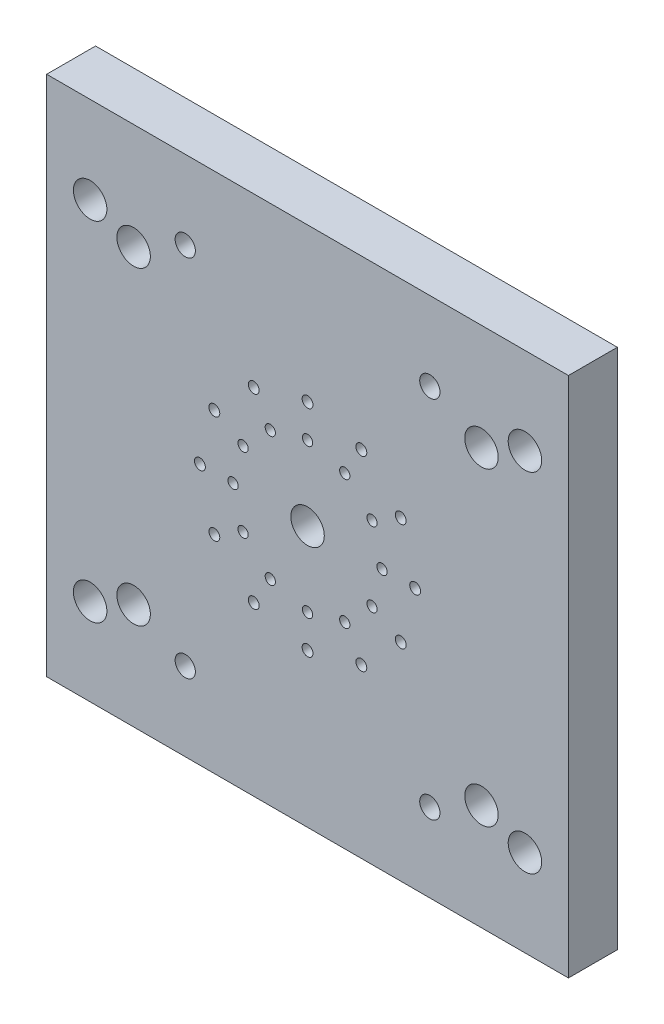
SolidWorks part; units mm, degrees
ref_plane "Front Plane" through (0, 0, 0) normal (0, 0, 1) x (1, 0, 0)
ref_plane "Top Plane" through (0, 0, 0) normal (0, 1, 0) x (1, 0, 0)
ref_plane "Right Plane" through (0, 0, 0) normal (1, 0, 0) x (0, 0, -1)
sketch "Sketch1" plane through (0, 0, 0) normal (0, 0, 1) x (1, 0, 0)
  line L1 (-152.4, 152.4) -> (152.4, 152.4)
  line L2 (-152.4, 152.4) -> (-152.4, -152.4)
  line L3 (-152.4, -152.4) -> (152.4, -152.4)
  line L4 (152.4, 152.4) -> (152.4, -152.4)
  line L5 (-152.4, 152.4) -> (152.4, -152.4) construction
  line L6 (-152.4, -152.4) -> (152.4, 152.4) construction
  point P0 (0, 0)
  dimension "D1" = 304.8
  dimension "D2" = 304.8
extrude "Boss-Extrude1" add sketch "Sketch1" along normal blind 28.575
sketch "Sketch2" plane through (0, 0, 28.575) normal (0, 0, 1) x (1, 0, 0)
  line L0 (-152.4, 0) -> (152.4, 0) construction
  line L5 (-152.4, 152.4) -> (-152.4, -152.4) construction
  line L6 (152.4, -152.4) -> (152.4, 152.4) construction
  line L7 (-152.4, -101.6) -> (152.4, -101.6) construction
  line L8 (-152.4, 101.6) -> (152.4, 101.6) construction
  line L9 (0, 101.6) -> (0, -101.6) construction
  line L10 (127, 101.6) -> (127, -101.6) construction
  line L11 (-127, 101.6) -> (-127, -101.6) construction
  circle A0 centre (-127, 101.6) radius 6.5151
  circle A1 centre (127, 101.6) radius 6.5151
  circle A2 centre (127, -101.6) radius 6.5151
  circle A3 centre (-127, -101.6) radius 6.5151
  circle A4 centre (0, 0) radius 6.5151
  dimension "D5" = 13.0302
  dimension "D1" = 101.6
  dimension "D2" = 101.6
  dimension "D3" = 127
  dimension "D4" = 127
extrude "HAAS T-Slot Holes" cut sketch "Sketch2" against normal through all
sketch "Sketch3" plane through (0, 0, 28.575) normal (0, 0, 1) x (1, 0, 0)
  circle A0 centre (-127, 101.6) radius 9.779
  circle A1 centre (127, 101.6) radius 9.779
  circle A2 centre (0, 0) radius 9.779
  circle A3 centre (127, -101.6) radius 9.779
  circle A4 centre (-127, -101.6) radius 9.779
  dimension "D1" = 19.558
extrude "HAAS Counter Bores" cut sketch "Sketch3" against normal offset from surface (19.05 mm away) 9.525 contours A0 | A1 | A2 | A3 | A4 up to face at (6.5151, 0, 0)
sketch "Sketch4" plane through (0, 0, 28.575) normal (0, 0, 1) x (1, 0, 0)
  line L0 (-127, 90.4875) -> (127, 90.4875) construction
  line L1 (-127, 30.1625) -> (127, 30.1625) construction
  line L2 (-127, 30.1625) -> (-127, -30.1625) construction
  line L3 (-127, -30.1625) -> (127, -30.1625) construction
  line L4 (127, 30.1625) -> (127, -30.1625) construction
  line L5 (-127, 30.1625) -> (127, -30.1625) construction
  line L6 (-127, -30.1625) -> (127, 30.1625) construction
  line L7 (-127, -90.4875) -> (127, -90.4875) construction
  line L8 (-101.6, 90.4875) -> (-101.6, 84.1375) construction
  line L9 (-101.6, -90.4875) -> (-101.6, -84.1375) construction
  line L10 (101.6, -90.4875) -> (101.6, -84.1375) construction
  line L11 (101.6, 90.4875) -> (101.6, 84.1375) construction
  circle A0 centre (-101.6, 90.4875) radius 6.5151
  circle A1 centre (101.6, 90.4875) radius 6.5151
  circle A2 centre (-101.6, -90.4875) radius 6.5151
  circle A3 centre (101.6, -90.4875) radius 6.5151
  point P0 (0, 0)
  dimension "D9" = 13.0302
  dimension "D1" = 60.325
  dimension "D2" = 254
  dimension "D5" = 203.2
  dimension "D6" = 25.4
  dimension "D7" = 203.2
  dimension "D8" = 6.35
  dimension "D3" = 60.325
  dimension "D4" = 60.325
extrude "Tormach T-Slot Holes" cut sketch "Sketch4" against normal through all
sketch "Sketch5" plane through (0, 0, 28.575) normal (0, 0, 1) x (1, 0, 0)
  circle A0 centre (-101.6, 90.4875) radius 9.779
  circle A1 centre (101.6, 90.4875) radius 9.779
  circle A2 centre (101.6, -90.4875) radius 9.779
  circle A3 centre (-101.6, -90.4875) radius 9.779
  dimension "D1" = 19.558
extrude "Tormach Counter bores" cut sketch "Sketch5" against normal up to surface (19.05 mm away) up to face at (-117.221, 101.6, 9.525)
sketch "Sketch6" plane through (0, 0, 28.575) normal (0, 0, 1) x (1, 0, 0)
  circle A0 centre (0, 0) radius 43.5 construction
  circle A1 centre (0, 43.5) radius 2.9997
  circle A2 centre (0, -43.5) radius 2.9997
  dimension "D1" = 87.0001
  dimension "D2" = 5.9995
extrude "Sprocket Locating Holes" cut sketch "Sketch6" against normal blind 19.05
sketch "Sketch7" plane through (0, 0, 28.575) normal (0, 0, 1) x (1, 0, 0)
  circle A0 centre (0, 0) radius 43.5 construction
  circle A2 centre (43.5, 0) radius 2.9997
  circle A4 centre (37.6721, -21.75) radius 2.9997
  circle A5 centre (21.75, -37.6721) radius 2.9997
  circle A6 centre (0, -43.5) radius 2.9997 [skipped]
  circle A7 centre (-21.75, -37.6721) radius 2.9997
  circle A8 centre (-37.6721, -21.75) radius 2.9997
  circle A9 centre (-43.5, 0) radius 2.9997
  circle A10 centre (-37.6721, 21.75) radius 2.9997
  circle A11 centre (-21.75, 37.6721) radius 2.9997
  circle A12 centre (0, 43.5) radius 2.9997 [skipped]
  circle A13 centre (21.75, 37.6721) radius 2.9997
  circle A14 centre (37.6721, 21.75) radius 2.9997
  point P31 (0, 0)
  dimension "D1" = 87.0001
  dimension "D2" = 5.9995
  dimension "D3" = 12
extrude "Sprocket Mounting clearance holes" cut sketch "Sketch7" against normal blind 19.05
sketch "Sketch8" plane through (0, 0, 28.575) normal (0, 0, 1) x (1, 0, 0)
  line L1 (-71.4375, 106.4641) -> (71.4375, 106.4641) construction
  line L2 (-71.4375, 106.4641) -> (-71.4375, -106.4641) construction
  line L3 (-71.4375, -106.4641) -> (71.4375, -106.4641) construction
  line L4 (71.4375, 106.4641) -> (71.4375, -106.4641) construction
  line L5 (-71.4375, 106.4641) -> (71.4375, -106.4641) construction
  line L6 (-71.4375, -106.4641) -> (71.4375, 106.4641) construction
  circle A0 centre (-71.4375, 106.4641) radius 5.9182
  circle A1 centre (71.4375, 106.4641) radius 5.9182
  circle A2 centre (71.4375, -106.4641) radius 5.9182
  circle A3 centre (-71.4375, -106.4641) radius 5.9182
  point P0 (0, 0)
  dimension "D3" = 11.8364
  dimension "D1" = 142.875
  dimension "D2" = 212.9282
extrude "1/2-13 Tapped Holes" cut sketch "Sketch8" against normal blind 19.05
sketch "Sketch9" plane through (0, 0, 28.575) normal (0, 0, 1) x (1, 0, 0)
  circle A0 centre (0, 0) radius 62.865 construction
  circle A1 centre (0, 62.865) radius 3.175
  circle A2 centre (31.4325, 54.4427) radius 3.175
  circle A4 centre (54.4427, 31.4325) radius 3.175
  circle A6 centre (62.865, 0) radius 3.175
  circle A8 centre (54.4427, -31.4325) radius 3.175
  circle A10 centre (31.4325, -54.4427) radius 3.175
  circle A12 centre (0, -62.865) radius 3.175
  circle A14 centre (-31.4325, -54.4427) radius 3.175
  circle A16 centre (-54.4427, -31.4325) radius 3.175
  circle A18 centre (-62.865, 0) radius 3.175
  circle A20 centre (-54.4427, 31.4325) radius 3.175
  circle A22 centre (-31.4325, 54.4427) radius 3.175
  point P30 (0, 0)
  point P40 (0, 0)
  dimension "D1" = 125.73
  dimension "D2" = 6.35
  dimension "D3" = 12
extrude "1/4-20 Sprocket Fixture Bolts" cut sketch "Sketch9" against normal blind 19.05
